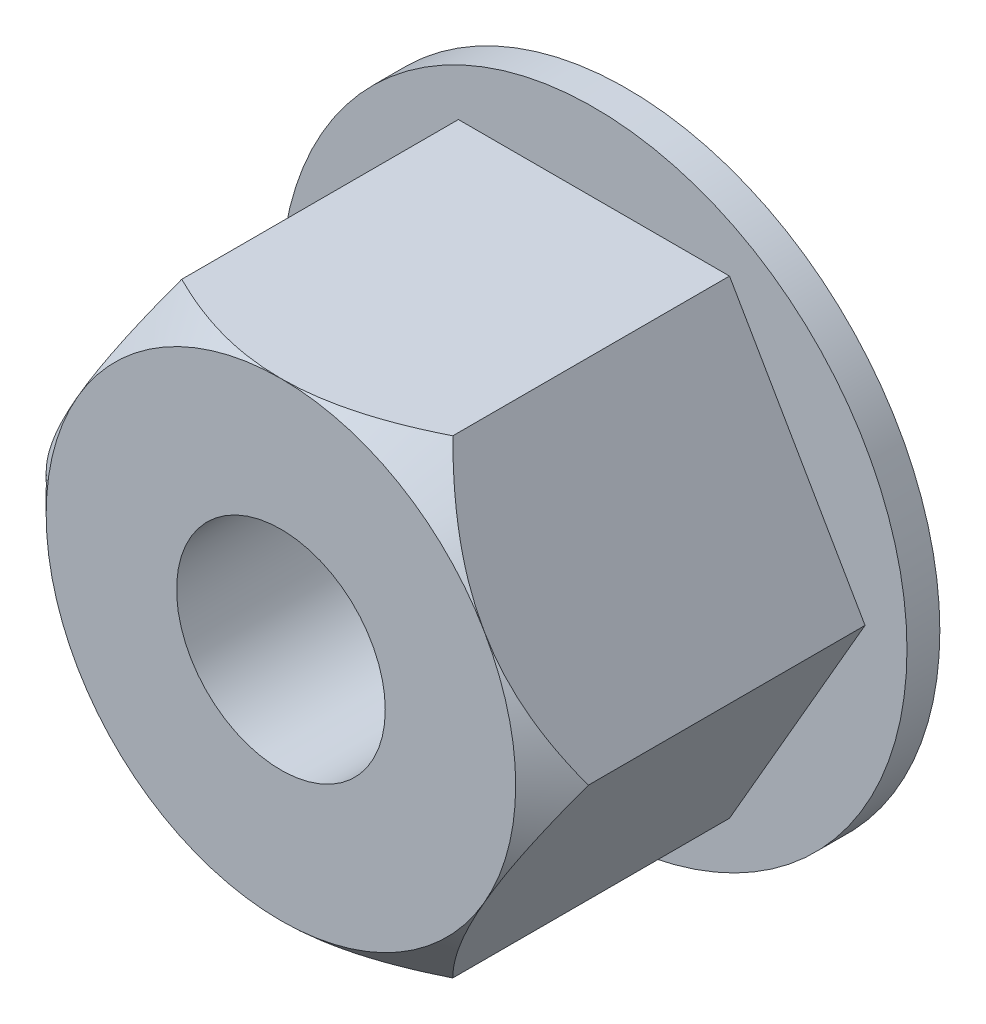
SolidWorks part; units mm, degrees
ref_plane "Front Plane" through (0, 0, 0) normal (0, 0, 1) x (1, 0, 0)
ref_plane "Top Plane" through (0, 0, 0) normal (0, 1, 0) x (1, 0, 0)
ref_plane "Right Plane" through (0, 0, 0) normal (1, 0, 0) x (0, 0, -1)
sketch "Sketch1" plane through (0, 0, 0) normal (0, 0, 1) x (1, 0, 0)
  circle A0 centre (0, 0) radius 9.525
  dimension "D1" = 19.05
extrude "Boss-Extrude1" add sketch "Sketch1" along normal blind 1
sketch "Sketch2" plane through (0, 0, 1) normal (0, 0, 1) x (1, 0, 0)
  line L1 (4.1244, -7.1438) -> (8.2489, 0)
  line L2 (8.2489, 0) -> (4.1244, 7.1438)
  line L3 (4.1244, 7.1438) -> (-4.1244, 7.1438)
  line L4 (-4.1244, 7.1438) -> (-8.2489, 0)
  line L5 (-8.2489, 0) -> (-4.1244, -7.1438)
  line L6 (-4.1244, -7.1438) -> (4.1244, -7.1438)
  circle A0 centre (0, 0) radius 7.1438 construction
  point P1 (0, 0)
extrude "Boss-Extrude2" add sketch "Sketch2" along normal blind 9.525
sketch "Sketch3" plane through (0, 0, 10.525) normal (0, 0, 1) x (1, 0, 0)
  circle A0 centre (0, 0) radius 3.175
  dimension "D1" = 6.35
extrude "Cut-Extrude1" cut sketch "Sketch3" against normal through all
sketch "Sketch4" plane through (0, 0, 10.525) normal (0, 0, 1) x (1, 0, 0)
  circle A0 centre (0, 0) radius 7.1438
extrude "Cut-Extrude2" cut sketch "Sketch4" against normal blind 9.525 draft 45 flip side to cut
